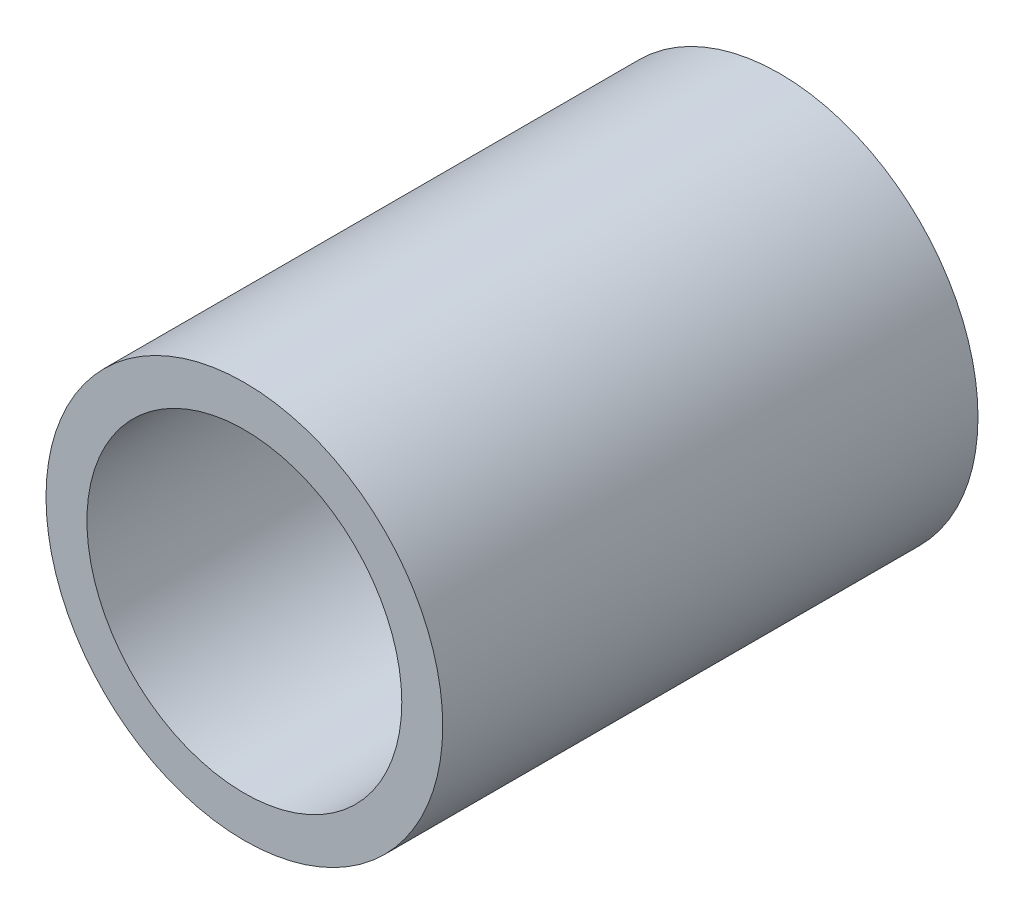
SolidWorks part; units mm, degrees
ref_plane "Płaszczyzna przednia" through (0, 0, 0) normal (0, 0, 1) x (1, 0, 0)
ref_plane "Płaszczyzna górna" through (0, 0, 0) normal (0, 1, 0) x (1, 0, 0)
ref_plane "Płaszczyzna prawa" through (0, 0, 0) normal (1, 0, 0) x (0, 0, -1)
sketch "Sketch1" plane through (0, 0, 0) normal (0, 0, 1) x (1, 0, 0)
  circle A0 centre (0, 0) radius 5
  circle A1 centre (0, 0) radius 6.3
  dimension "D1" = 10
  dimension "D2" = 1.3
extrude "Boss-Extrude1" add sketch "Sketch1" along normal blind 17
